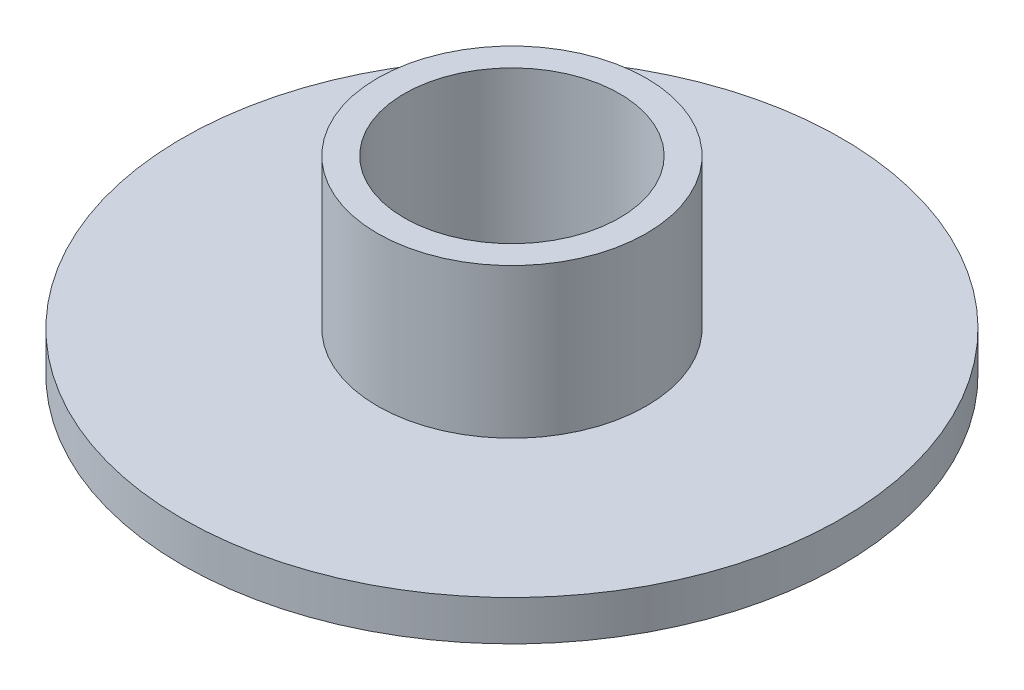
SolidWorks part; units mm, degrees
ref_plane "Front Plane" through (0, 0, 0) normal (0, 0, 1) x (1, 0, 0)
ref_plane "Top Plane" through (0, 0, 0) normal (0, 1, 0) x (1, 0, 0)
ref_plane "Right Plane" through (0, 0, 0) normal (1, 0, 0) x (0, 0, -1)
sketch "Sketch12" plane through (0, 0, 0) normal (0, 0, 1) x (1, 0, 0)
  line L0 (0, 43.1884) -> (0, 0)
  line L1 (0, 0) -> (52.5972, 0)
  line L2 (52.5972, 0) -> (52.5972, 9.525)
  line L3 (52.5972, 9.525) -> (6.35, 9.525)
  line L4 (6.35, 9.525) -> (6.35, 44.969)
  line L5 (6.35, 44.969) -> (0, 44.969)
  line L6 (0, 44.969) -> (0, 43.1884)
  line L7 (-25.5258, 53.4268) -> (-25.5258, -17.574) construction
revolve "Revolve1" add sketch "Sketch12" angle 360 about L7
sketch "Sketch13" plane through (0, 0, 0) normal (0, 0, 1) x (1, 0, 0)
  line L0 (6.35, 38.795) -> (44.2762, 9.525)
  line L1 (6.35, 9.525) -> (6.35, 44.969) construction
  line L2 (52.5972, 9.525) -> (-103.6489, 9.525) construction
